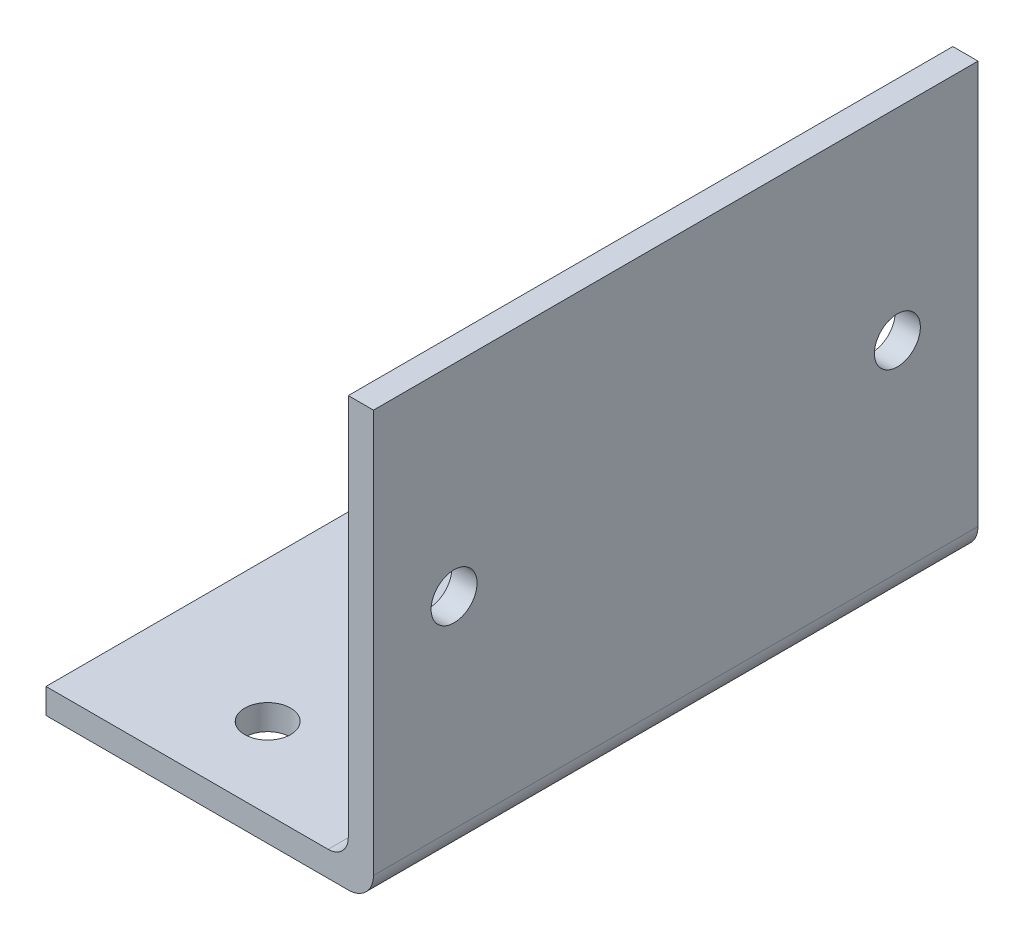
SolidWorks part; units mm, degrees
ref_plane "Front Plane" through (0, 0, 0) normal (0, 0, 1) x (1, 0, 0)
ref_plane "Top Plane" through (0, 0, 0) normal (0, 1, 0) x (1, 0, 0)
ref_plane "Right Plane" through (0, 0, 0) normal (1, 0, 0) x (0, 0, -1)
sketch "Sketch1" plane through (0, 0, 0) normal (0, 0, 1) x (1, 0, 0)
  line L0 (0, 0) -> (38.1, 0)
  line L1 (41.275, 3.175) -> (41.275, 53.975)
  line L2 (41.275, 53.975) -> (38.1, 53.975)
  line L3 (38.1, 53.975) -> (38.1, 5.715)
  line L4 (35.56, 3.175) -> (0, 3.175)
  line L5 (0, 3.175) -> (0, 0)
  arc A0 (38.1, 0) -> (41.275, 3.175) centre (38.1, 3.175) ccw
  arc A1 (35.56, 3.175) -> (38.1, 5.715) centre (35.56, 5.715) ccw
  dimension "D4" = 2.54
  dimension "D1" = 3.175
  dimension "D2" = 38.1
  dimension "D3" = 50.8
extrude "Boss-Extrude1" add sketch "Sketch1" along normal blind 76.2
sketch "Sketch2" plane through (0, 3.175, 0) normal (0, 1, 0) x (1, 0, 0)
  line L0 (17.78, 0) -> (17.78, -76.2) construction
  line L1 (35.56, 0) -> (0, 0) construction
  line L2 (35.56, -76.2) -> (0, -76.2) construction
  point P2 (17.78, -66.04)
  point P5 (17.78, -38.1)
  point P8 (17.78, -10.16)
  dimension "D1" = 27.94
  dimension "D2" = 27.94
sketch "Sketch3" plane through (41.275, 0, 0) normal (1, 0, 0) x (0, 0, -1)
  line L0 (-76.2, 28.575) -> (0, 28.575) construction
  line L1 (0, 3.175) -> (0, 53.975) construction
  line L4 (-76.2, 3.175) -> (-76.2, 53.975) construction
  point P2 (-10.16, 28.575)
  point P3 (-38.1, 28.575)
  point P4 (-66.04, 28.575)
  point P5 (0, 0)
  point P6 (0, 0)
  point P9 (0, 0)
  point P12 (-76.2, 31.75)
  dimension "D1" = 27.94
  dimension "D2" = 27.94
hole_wizard "#12 Clearance Hole1" positions "3DSketch1" profile "Sketch4" hole size "#12" standard "ANSI Inch"
sketch3d "3DSketch1"
  point P0 (41.275, 28.575, 10.16)
  point P3 (41.275, 28.575, 66.04)
  point P6 (17.78, 3.175, 66.04)
  point P9 (17.78, 3.175, 10.16)
sketch "Sketch4" plane through (41.275, 28.575, 10.16) normal (0, 1, 0) x (0, 0, -1)
  line L0 (0, 0) -> (0, 69.85)
  line L1 (0, 69.85) -> (2.8956, 68.1101)
  line L2 (2.8956, 68.1101) -> (2.8956, 0)
  line L5 (2.8956, 0) -> (0, 0)
  line L10 (0, 69.85) -> (-2.8956, 68.1101) construction
  line L11 (0, -6.35) -> (0, 107.95) construction
  dimension "Hole Dia." = 5.7912
  dimension "Hole Depth" = 69.85
  dimension "Drill Angle" = 118
